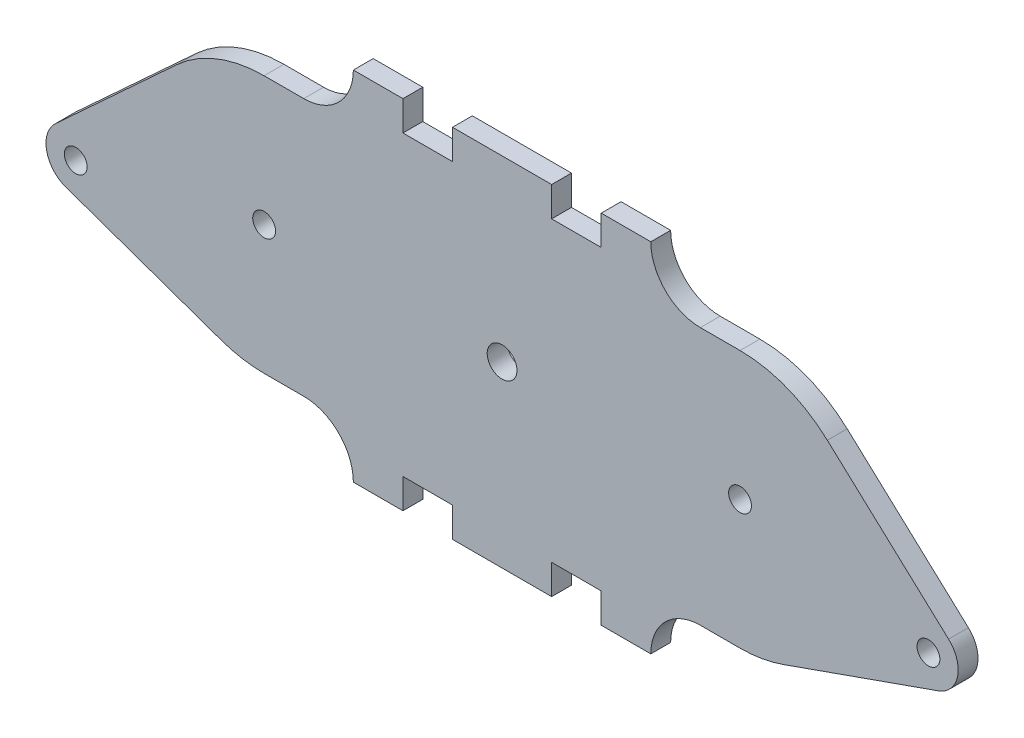
SolidWorks part; units mm, degrees
ref_plane "Спереди" through (0, 0, 0) normal (0, 0, 1) x (1, 0, 0)
ref_plane "Сверху" through (0, 0, 0) normal (0, 1, 0) x (1, 0, 0)
ref_plane "Справа" through (0, 0, 0) normal (1, 0, 0) x (0, 0, -1)
sketch "Model" plane through (0, 0, 0) normal (0, 0, 1) x (1, 0, 0)
  line L0 (-15, 18) -> (-10, 18)
  line L1 (-10, 18) -> (-10, 15)
  line L2 (-5, 15) -> (-5, 18)
  line L3 (-5, 18) -> (5, 18)
  line L4 (5, 18) -> (5, 15)
  line L5 (5, 15) -> (10, 15)
  line L6 (10, -15) -> (5, -15)
  line L7 (5, -15) -> (5, -18)
  line L8 (5, -18) -> (-5, -18)
  line L9 (-5, -18) -> (-5, -15)
  line L10 (-10, -15) -> (-10, -18)
  line L11 (-10, -18) -> (-15, -18)
  line L12 (-45.032, -1.6929) -> (-32.8052, 9.5639)
  line L13 (-43.9982, -6.729) -> (-28.3257, -12.2592)
  line L14 (-10, -15) -> (-5, -15)
  line L15 (-10, -18) -> (-15, -18)
  line L16 (-24, -13) -> (-20, -13)
  line L17 (-10, 18) -> (-15, 18)
  line L18 (-20, 13) -> (-24, 13)
  line L19 (-10, 15) -> (-5, 15)
  line L20 (15, 18) -> (10, 18)
  line L21 (10, 18) -> (10, 15)
  line L22 (10, -15) -> (10, -18)
  line L23 (10, -18) -> (15, -18)
  line L24 (45.032, -1.6929) -> (32.8052, 9.5639)
  line L25 (43.9982, -6.729) -> (28.3257, -12.2592)
  line L26 (10, -18) -> (15, -18)
  line L27 (24, -13) -> (20, -13)
  line L28 (10, 18) -> (15, 18)
  line L29 (20, 13) -> (24, 13)
  circle A0 centre (0, 0) radius 1.5
  circle A1 centre (-24, 0) radius 1.15
  circle A2 centre (-43, -3.9) radius 1.15
  arc A3 (-45.032, -1.6929) -> (-43.9982, -6.729) centre (-43, -3.9) ccw
  arc A4 (-28.3257, -12.2592) -> (-24, -13) centre (-24, 0) ccw
  arc A5 (-45.032, -1.6929) -> (-43.9982, -6.729) centre (-43, -3.9) ccw
  arc A6 (-15, -18) -> (-20, -13) centre (-20, -18) ccw
  arc A7 (-20, 13) -> (-15, 18) centre (-20, 18) ccw
  arc A8 (-24, 13) -> (-32.8052, 9.5639) centre (-24, 0) ccw
  circle A9 centre (24, 0) radius 1.15
  circle A10 centre (43, -3.9) radius 1.15
  arc A11 (43.9982, -6.729) -> (45.032, -1.6929) centre (43, -3.9) ccw
  arc A12 (24, -13) -> (28.3257, -12.2592) centre (24, 0) ccw
  arc A13 (43.9982, -6.729) -> (45.032, -1.6929) centre (43, -3.9) ccw
  arc A14 (20, -13) -> (15, -18) centre (20, -18) ccw
  arc A15 (15, 18) -> (20, 13) centre (20, 18) ccw
  arc A16 (32.8052, 9.5639) -> (24, 13) centre (24, 0) ccw
  circle A17 centre (-24, 0) radius 13
extrude "Бобышка-Вытянуть1" add sketch "Model" along normal blind 2 contours A8 A17 A4 A1 | A17 L12 A3 L13 A2 | A17 L16 A6 L11 L10 L14 L9 L8 L7 L6 L22 L23 A14 L27 A12 L25 A11 L24 A16 L29 A15 L20 L21 L5 L4 L3 L2 L19 L1 L0 A7 L18 A0 A9 A10
